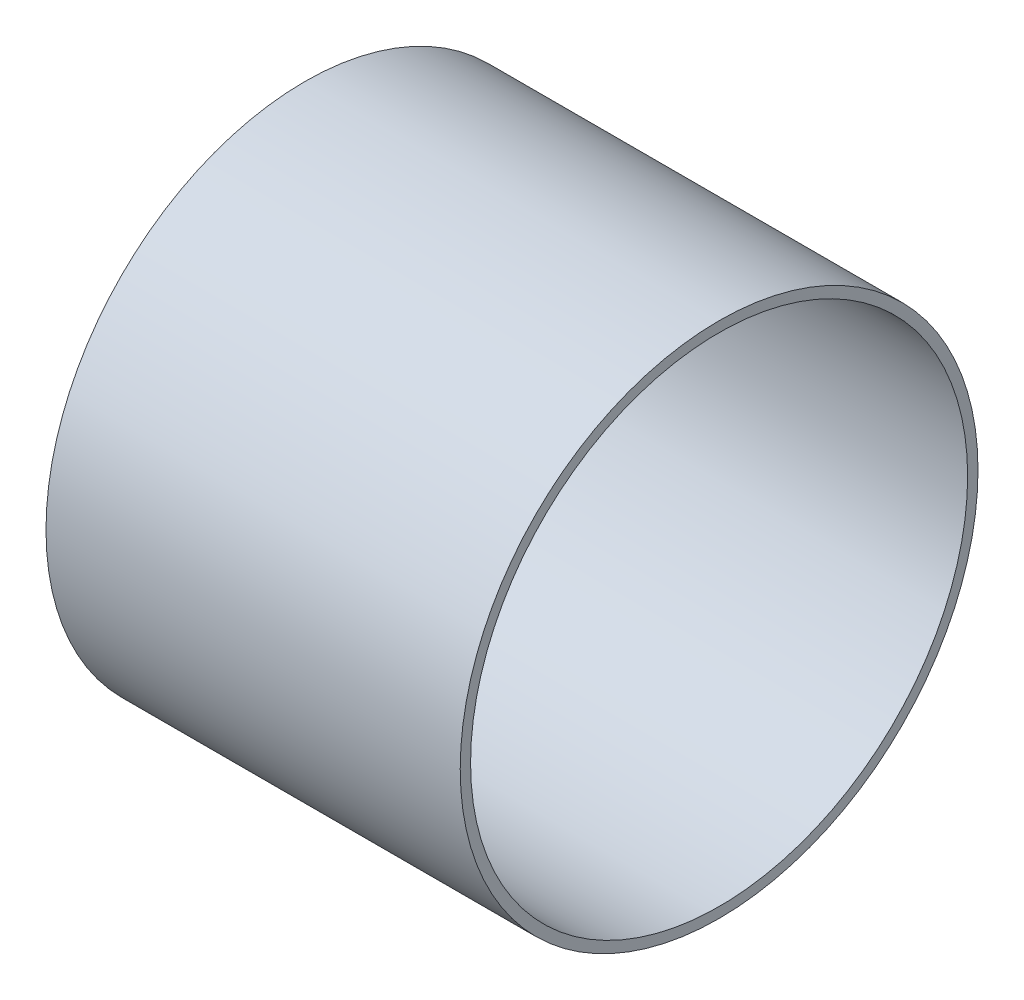
SolidWorks part; units mm, degrees
material "Cast Alloy Steel"
ref_plane "Front" through (0, 0, 0) normal (0, 0, 1) x (1, 0, 0)
ref_plane "Top" through (0, 0, 0) normal (0, 1, 0) x (1, 0, 0)
ref_plane "Right" through (0, 0, 0) normal (1, 0, 0) x (0, 0, -1)
sketch "Sketch1" plane through (0, 0, 0) normal (1, 0, 0) x (0, 0, -1)
  circle A0 centre (0, 0) radius 25
  dimension "D1" = 50
extrude "Boss-Extrude1" add sketch "Sketch1" against normal blind 40
sketch "Sketch2" plane through (0, 0, 0) normal (1, 0, 0) x (0, 0, -1)
  circle A2 centre (0, 0) radius 24
  circle A3 centre (0, 0) radius 24
  dimension "D1" = 1
extrude "Cut-Extrude1" cut sketch "Sketch2" against normal through all
